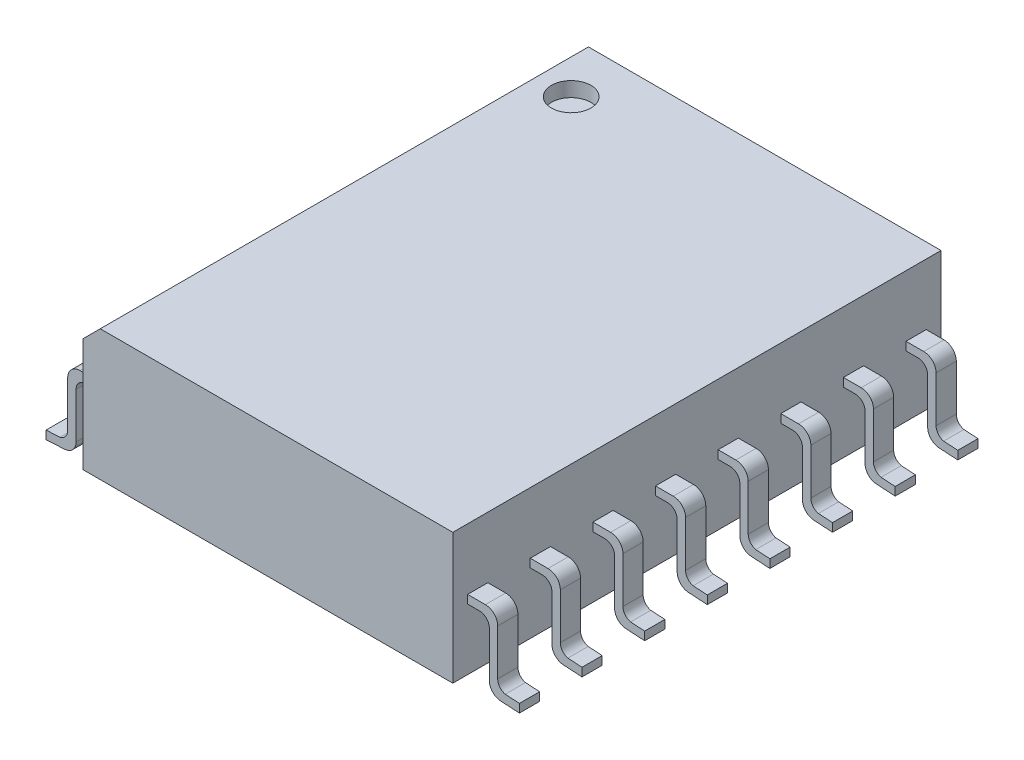
SolidWorks part; units mm, degrees
ref_plane "Plano frontal" through (0, 0, 0) normal (0, 0, 1) x (1, 0, 0)
ref_plane "Plano superior" through (0, 0, 0) normal (0, 1, 0) x (1, 0, 0)
ref_plane "Plano direito" through (0, 0, 0) normal (1, 0, 0) x (0, 0, -1)
ref_plane "Body_Plane" through (0, 0.15, 0) normal (0, 1, 0) x (-1, 0, 0)
sketch "Sketch2" plane through (0, 0.15, 0) normal (0, 1, 0) x (1, 0, 0)
  line L1 (3.75, -4.95) -> (-3.75, -4.95)
  line L2 (3.75, -4.95) -> (3.75, 4.95)
  line L3 (3.75, 4.95) -> (-3.75, 4.95)
  line L4 (-3.75, -4.95) -> (-3.75, 4.95)
  line L5 (3.75, -4.95) -> (-3.75, 4.95) construction
  line L6 (3.75, 4.95) -> (-3.75, -4.95) construction
  point P0 (0, 0)
  dimension "D1" = 9.9
  dimension "D2" = 7.5
extrude "Body" add sketch "Sketch2" along normal blind 2.65
ref_plane "Lead_1_Plane" through (0, 0, 4.445) normal (0, 0, 1) x (1, 0, 0)
sketch "Sketch3" plane through (0, 0, 4.445) normal (0, 0, 1) x (1, 0, 0)
  line L0 (3.75, 2.8) -> (3.75, 0) construction
  line L1 (4.8, 1.4437) -> (4.8, 0) construction
  line L2 (3.75, 1.56) -> (4.1102, 1.56)
  line L3 (3.75, 1.39) -> (3.99, 1.39)
  line L4 (4.19, 1.19) -> (4.19, 0.2675)
  line L5 (4.4197, 0.0233) -> (4.8, 0)
  line L6 (3.75, 0) -> (4.8, 0) construction
  line L7 (4.36, 1.3102) -> (4.36, 0.3823)
  line L8 (4.5134, 0.1878) -> (4.8, 0.1703)
  line L9 (4.8, 0.1703) -> (4.8, 0)
  line L10 (3.75, 1.39) -> (3.75, 1.56)
  line L11 (2.5431, 0.138) -> (2.6866, 0.1293) construction
  line L13 (3.75, 2.8) -> (3.75, 0.15) construction
  line L14 (-3.75, 0.15) -> (3.75, 0.15) construction
  arc A0 (3.99, 1.39) -> (4.19, 1.19) centre (3.99, 1.19) cw
  arc A1 (4.19, 0.2675) -> (4.4197, 0.0233) centre (4.4347, 0.2675) ccw
  arc A2 (4.1102, 1.56) -> (4.36, 1.3102) centre (4.1102, 1.3102) cw
  arc A3 (4.36, 0.3823) -> (4.5134, 0.1878) centre (4.56, 0.3823) ccw
  point P8 (4.4197, 0.0233)
  point P21 (3.75, 1.475)
  dimension "D3" = 0.2
  dimension "D4" = 0.2
  dimension "D11" = 0.17
  dimension "D9" = 0.17
  dimension "D1" = 1.05
  dimension "D2" = 3.5
  dimension "D5" = 0.61
  dimension "D6" = 0.17
  dimension "D7" = 0.17
  dimension "D8" = 0.085
  dimension "D10" = 0.17
  dimension "D12" = 0.15
  dimension "D13" = 0
extrude "Lead" add sketch "Sketch3" along normal mid plane 0.41
pattern_linear "SD_Leads" count 8 spacing 1.27 along (0, 0, -1) of "Lead"
mirror "Mirror1" about plane through (0, 0, 0) normal (1, 0, 0) of "SD_Leads", "Lead"
sketch "Sketch4" plane through (0, 2.8, 0) normal (0, 1, 0) x (1, 0, 0)
  line L0 (-3.75, 3.9008) -> (-2.7008, 3.9008) construction
  line L1 (-3.75, 4.95) -> (-3.75, -4.95) construction
  line L2 (-2.7008, 3.9008) -> (-2.7008, 4.95) construction
  line L3 (3.75, 4.95) -> (-3.75, 4.95) construction
  circle A0 centre (-2.7008, 3.9008) radius 0.4
extrude "Cut-Extrude1" cut sketch "Sketch4" against normal blind 0.3
chamfer "Chamfer1" distance 0.35 angle 45 1 edges at (-3.75, 2.8, 0)
equation "\"BODY_X\" = 7.5"
equation "\"BODY_Z\"= 9.9"
equation "\"BODY_THICKNESS\" = 2.65"
equation "\"NUM_LEADS\"= 16"
equation "\"PITCH\"= 1.27"
equation "\"LEAD_WIDTH\"= 0.41"
equation "\"LEAD_THICKNESS\"= 0.17"
equation "\"LEAD_LENGTH\"= 1.05"
equation "\"LEAD_BODY_OFFSET\"= 0.15"
equation "\"D1@Sketch2\" = \"BODY_Z\""
equation "\"D2@Sketch2\" = \"BODY_X\""
equation "\"D6@Sketch3\" = \"LEAD_THICKNESS\""
equation "\"D7@Sketch3\" = \"LEAD_THICKNESS\""
equation "\"D9@Sketch3\" = \"LEAD_THICKNESS\""
equation "\"D10@Sketch3\" = \"LEAD_THICKNESS\""
equation "\"D11@Sketch3\" = \"LEAD_THICKNESS\""
equation "\"D1@Sketch3\" = \"LEAD_LENGTH\""
equation "\"D1@LEAD\" = \"LEAD_WIDTH\""
equation "\"LEADS_SIDE\"= \"NUM_LEADS\" / 2"
equation "\"D1@Lead_1_Plane\" = ( \"BODY_Z\" - ( \"LEADS_SIDE\" * \"PITCH\" - \"PITCH\" + \"LEAD_WIDTH\" ) + \"LEAD_WIDTH\" ) / 2"
equation "\"D1@SD_Leads\" = \"LEADS_SIDE\""
equation "\"D3@SD_Leads\" = \"PITCH\""
equation "\"D1@Body\" = \"BODY_THICKNESS\""
equation "\"D12@Sketch3\" = \"LEAD_BODY_OFFSET\""
equation "\"D1@Body_Plane\" = \"LEAD_BODY_OFFSET\""
equation "\"D5@Sketch3\" = ( \"LEAD_LENGTH\" + \"LEAD_THICKNESS\" ) / 2"
